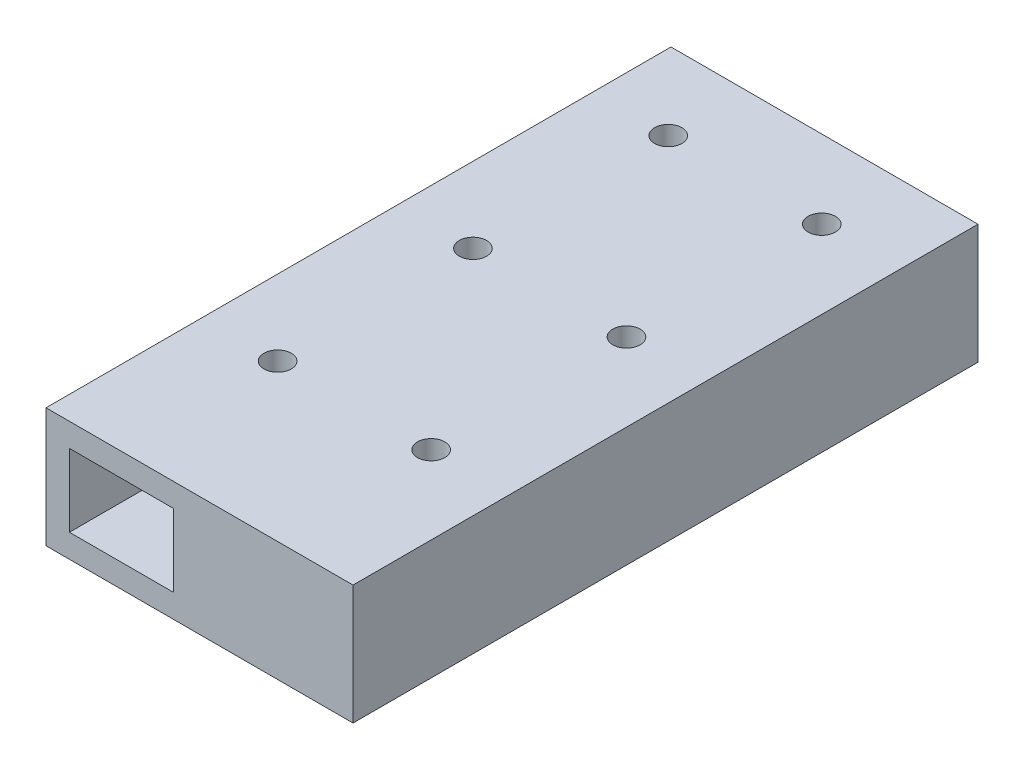
SolidWorks part; units mm, degrees
ref_plane "前视基准面" through (0, 0, 0) normal (0, 0, 1) x (1, 0, 0)
ref_plane "上视基准面" through (0, 0, 0) normal (0, 1, 0) x (1, 0, 0)
ref_plane "右视基准面" through (0, 0, 0) normal (1, 0, 0) x (0, 0, -1)
sketch "草图2" plane through (0, 0, 0) normal (0, 0, 1) x (1, 0, 0)
  line L5 (-9.65, -7.65) -> (9.65, -7.65)
  line L6 (-9.65, -7.65) -> (-9.65, 7.65)
  line L7 (-6.65, -4.65) -> (6.65, -4.65)
  line L8 (-6.65, -4.65) -> (-6.65, 4.65)
  line L9 (-6.65, 4.65) -> (6.65, 4.65)
  line L10 (6.65, -4.65) -> (6.65, 4.65)
  line L11 (-6.65, -4.65) -> (6.65, 4.65) construction
  line L12 (-6.65, 4.65) -> (6.65, -4.65) construction
  line L13 (-9.65, 7.65) -> (9.65, 7.65)
  line L14 (9.65, -7.65) -> (9.65, 7.65)
  line L15 (-9.65, -7.65) -> (9.65, 7.65) construction
  line L16 (-9.65, 7.65) -> (9.65, -7.65) construction
  point P0 (0, 0)
  point P1 (0, 0)
  point P6 (0, 0)
  dimension "D1" = 13.3
  dimension "D2" = 9.3
  dimension "D3" = 3
  dimension "D4" = 3
extrude "凸台-拉伸1" add sketch "草图2" along normal blind 80
sketch "草图3" plane through (0, 7.65, 0) normal (0, 1, 0) x (1, 0, 0)
  line L0 (0, 2.2879) -> (0, -86.2136) construction
  line L1 (9.65, 0) -> (-9.65, 0) construction
  circle A0 centre (0, -10) radius 1.75
  circle A1 centre (0, -35) radius 1.75
  circle A2 centre (0, -60) radius 1.75
  point P9 (0, 2.2879)
  point P10 (0, -9.3116)
  dimension "D1" = 25
  dimension "D2" = 3.5
  dimension "D3" = 25
  dimension "D4" = 10
  dimension "D5" = 3.5
  dimension "D6" = 3.5
extrude "切除-拉伸1" cut sketch "草图3" against normal blind 100
sketch "草图5" plane through (0, 0, 0) normal (0, 0, -1) x (-1, 0, 0)
  line L1 (-9.65, -7.65) -> (-29.65, -7.65)
  line L2 (-9.65, -7.65) -> (-9.65, 7.65)
  line L3 (-9.65, 7.65) -> (-29.65, 7.65)
  line L4 (-29.65, -7.65) -> (-29.65, 7.65)
  dimension "D1" = 20
extrude "凸台-拉伸2" add sketch "草图5" against normal up to surface (80 mm away) up to face at (0, 0, 80)
sketch "草图6" plane through (0, 7.65, 0) normal (0, 1, 0) x (1, 0, 0)
  line L0 (29.65, 0) -> (-9.65, 0) construction
  line L1 (29.65, -80) -> (29.65, 0) construction
  circle A0 centre (19.65, -10) radius 1.75
  circle A1 centre (19.65, -35) radius 1.75
  circle A3 centre (19.65, -60) radius 1.75
  dimension "D1" = 3.5
  dimension "D2" = 3.5
  dimension "D3" = 3.5
  dimension "D4" = 25
  dimension "D5" = 25
  dimension "D6" = 10
  dimension "D7" = 10
extrude "切除-拉伸2" cut sketch "草图6" against normal blind 100
